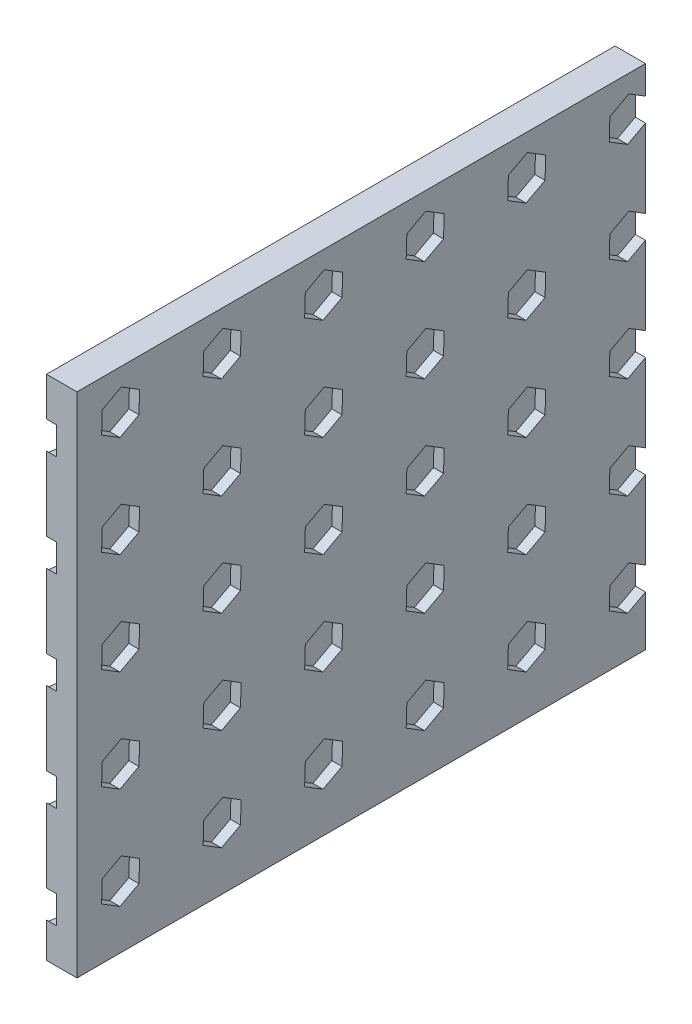
SolidWorks part; units mm, degrees
ref_plane "Front Plane" through (0, 0, 0) normal (0, 0, 1) x (1, 0, 0)
ref_plane "Top Plane" through (0, 0, 0) normal (0, 1, 0) x (1, 0, 0)
ref_plane "Right Plane" through (0, 0, 0) normal (1, 0, 0) x (0, 0, -1)
sketch "Sketch1" plane through (0, 0, 0) normal (1, 0, 0) x (0, 0, -1)
  line L1 (-28, 25) -> (28, 25)
  line L2 (-28, 25) -> (-28, -25)
  line L3 (-28, -25) -> (28, -25)
  line L4 (28, 25) -> (28, -25)
  line L5 (0, -25) -> (0, 25) construction
  line L6 (-28, 0) -> (28, 0) construction
  point P0 (0, 0)
  dimension "D1" = 56
  dimension "D2" = 50
extrude "Boss-Extrude1" add sketch "Sketch1" along normal blind 3
sketch "Sketch2" plane through (3, 0, 0) normal (1, 0, 0) x (0, 0, -1)
  line L0 (-11.8942, 19.989) -> (-11.829, 22.1127)
  line L1 (-21.8942, 19.989) -> (-21.829, 22.1127)
  line L2 (-21.829, 22.1127) -> (-23.6355, 23.231)
  line L3 (-23.6355, 23.231) -> (-25.5072, 22.2257)
  line L4 (-25.5072, 22.2257) -> (-25.5725, 20.102)
  line L5 (-25.5725, 20.102) -> (-23.766, 18.9837)
  line L6 (-23.766, 18.9837) -> (-21.8942, 19.989)
  line L7 (-11.829, 22.1127) -> (-13.6355, 23.231)
  line L8 (-13.6355, 23.231) -> (-15.5072, 22.2257)
  line L9 (-15.5072, 22.2257) -> (-15.5725, 20.102)
  line L10 (-15.5725, 20.102) -> (-13.766, 18.9837)
  line L11 (-13.766, 18.9837) -> (-11.8942, 19.989)
  line L12 (-1.8942, 19.989) -> (-1.829, 22.1127)
  line L13 (-1.829, 22.1127) -> (-3.6355, 23.231)
  line L14 (-3.6355, 23.231) -> (-5.5072, 22.2257)
  line L15 (-5.5072, 22.2257) -> (-5.5725, 20.102)
  line L16 (-5.5725, 20.102) -> (-3.766, 18.9837)
  line L17 (-3.766, 18.9837) -> (-1.8942, 19.989)
  line L18 (8.1058, 19.989) -> (8.171, 22.1127)
  line L19 (8.171, 22.1127) -> (6.3645, 23.231)
  line L20 (6.3645, 23.231) -> (4.4928, 22.2257)
  line L21 (4.4928, 22.2257) -> (4.4275, 20.102)
  line L22 (4.4275, 20.102) -> (6.234, 18.9837)
  line L23 (6.234, 18.9837) -> (8.1058, 19.989)
  line L24 (18.1058, 19.989) -> (18.171, 22.1127)
  line L25 (18.171, 22.1127) -> (16.3645, 23.231)
  line L26 (16.3645, 23.231) -> (14.4928, 22.2257)
  line L27 (14.4928, 22.2257) -> (14.4275, 20.102)
  line L28 (14.4275, 20.102) -> (16.234, 18.9837)
  line L29 (16.234, 18.9837) -> (18.1058, 19.989)
  line L30 (28.1058, 19.989) -> (28.171, 22.1127)
  line L31 (28.171, 22.1127) -> (26.3645, 23.231)
  line L32 (26.3645, 23.231) -> (24.4928, 22.2257)
  line L33 (24.4928, 22.2257) -> (24.4275, 20.102)
  line L34 (24.4275, 20.102) -> (26.234, 18.9837)
  line L35 (26.234, 18.9837) -> (28.1058, 19.989)
  line L36 (-11.8942, 9.989) -> (-11.829, 12.1127)
  line L37 (-11.829, 12.1127) -> (-13.6355, 13.231)
  line L38 (-13.6355, 13.231) -> (-15.5072, 12.2257)
  line L39 (-15.5072, 12.2257) -> (-15.5725, 10.102)
  line L40 (-15.5725, 10.102) -> (-13.766, 8.9837)
  line L41 (-13.766, 8.9837) -> (-11.8942, 9.989)
  line L42 (-1.8942, 9.989) -> (-1.829, 12.1127)
  line L43 (-1.829, 12.1127) -> (-3.6355, 13.231)
  line L44 (-3.6355, 13.231) -> (-5.5072, 12.2257)
  line L45 (-5.5072, 12.2257) -> (-5.5725, 10.102)
  line L46 (-5.5725, 10.102) -> (-3.766, 8.9837)
  line L47 (-3.766, 8.9837) -> (-1.8942, 9.989)
  line L48 (8.1058, 9.989) -> (8.171, 12.1127)
  line L49 (8.171, 12.1127) -> (6.3645, 13.231)
  line L50 (6.3645, 13.231) -> (4.4928, 12.2257)
  line L51 (4.4928, 12.2257) -> (4.4275, 10.102)
  line L52 (4.4275, 10.102) -> (6.234, 8.9837)
  line L53 (6.234, 8.9837) -> (8.1058, 9.989)
  line L54 (18.1058, 9.989) -> (18.171, 12.1127)
  line L55 (18.171, 12.1127) -> (16.3645, 13.231)
  line L56 (16.3645, 13.231) -> (14.4928, 12.2257)
  line L57 (14.4928, 12.2257) -> (14.4275, 10.102)
  line L58 (14.4275, 10.102) -> (16.234, 8.9837)
  line L59 (16.234, 8.9837) -> (18.1058, 9.989)
  line L60 (28.1058, 9.989) -> (28.171, 12.1127)
  line L61 (28.171, 12.1127) -> (26.3645, 13.231)
  line L62 (26.3645, 13.231) -> (24.4928, 12.2257)
  line L63 (24.4928, 12.2257) -> (24.4275, 10.102)
  line L64 (24.4275, 10.102) -> (26.234, 8.9837)
  line L65 (26.234, 8.9837) -> (28.1058, 9.989)
  line L66 (-11.8942, -0.011) -> (-11.829, 2.1127)
  line L67 (-11.829, 2.1127) -> (-13.6355, 3.231)
  line L68 (-13.6355, 3.231) -> (-15.5072, 2.2257)
  line L69 (-15.5072, 2.2257) -> (-15.5725, 0.102)
  line L70 (-15.5725, 0.102) -> (-13.766, -1.0163)
  line L71 (-13.766, -1.0163) -> (-11.8942, -0.011)
  line L72 (-1.8942, -0.011) -> (-1.829, 2.1127)
  line L73 (-1.829, 2.1127) -> (-3.6355, 3.231)
  line L74 (-3.6355, 3.231) -> (-5.5072, 2.2257)
  line L75 (-5.5072, 2.2257) -> (-5.5725, 0.102)
  line L76 (-5.5725, 0.102) -> (-3.766, -1.0163)
  line L77 (-3.766, -1.0163) -> (-1.8942, -0.011)
  line L78 (8.1058, -0.011) -> (8.171, 2.1127)
  line L79 (8.171, 2.1127) -> (6.3645, 3.231)
  line L80 (6.3645, 3.231) -> (4.4928, 2.2257)
  line L81 (4.4928, 2.2257) -> (4.4275, 0.102)
  line L82 (4.4275, 0.102) -> (6.234, -1.0163)
  line L83 (6.234, -1.0163) -> (8.1058, -0.011)
  line L84 (18.1058, -0.011) -> (18.171, 2.1127)
  line L85 (18.171, 2.1127) -> (16.3645, 3.231)
  line L86 (16.3645, 3.231) -> (14.4928, 2.2257)
  line L87 (14.4928, 2.2257) -> (14.4275, 0.102)
  line L88 (14.4275, 0.102) -> (16.234, -1.0163)
  line L89 (16.234, -1.0163) -> (18.1058, -0.011)
  line L90 (28.1058, -0.011) -> (28.171, 2.1127)
  line L91 (28.171, 2.1127) -> (26.3645, 3.231)
  line L92 (26.3645, 3.231) -> (24.4928, 2.2257)
  line L93 (24.4928, 2.2257) -> (24.4275, 0.102)
  line L94 (24.4275, 0.102) -> (26.234, -1.0163)
  line L95 (26.234, -1.0163) -> (28.1058, -0.011)
  line L96 (-11.8942, -10.011) -> (-11.829, -7.8873)
  line L97 (-11.829, -7.8873) -> (-13.6355, -6.769)
  line L98 (-13.6355, -6.769) -> (-15.5072, -7.7743)
  line L99 (-15.5072, -7.7743) -> (-15.5725, -9.898)
  line L100 (-15.5725, -9.898) -> (-13.766, -11.0163)
  line L101 (-13.766, -11.0163) -> (-11.8942, -10.011)
  line L102 (-1.8942, -10.011) -> (-1.829, -7.8873)
  line L103 (-1.829, -7.8873) -> (-3.6355, -6.769)
  line L104 (-3.6355, -6.769) -> (-5.5072, -7.7743)
  line L105 (-5.5072, -7.7743) -> (-5.5725, -9.898)
  line L106 (-5.5725, -9.898) -> (-3.766, -11.0163)
  line L107 (-3.766, -11.0163) -> (-1.8942, -10.011)
  line L108 (8.1058, -10.011) -> (8.171, -7.8873)
  line L109 (8.171, -7.8873) -> (6.3645, -6.769)
  line L110 (6.3645, -6.769) -> (4.4928, -7.7743)
  line L111 (4.4928, -7.7743) -> (4.4275, -9.898)
  line L112 (4.4275, -9.898) -> (6.234, -11.0163)
  line L113 (6.234, -11.0163) -> (8.1058, -10.011)
  line L114 (18.1058, -10.011) -> (18.171, -7.8873)
  line L115 (18.171, -7.8873) -> (16.3645, -6.769)
  line L116 (16.3645, -6.769) -> (14.4928, -7.7743)
  line L117 (14.4928, -7.7743) -> (14.4275, -9.898)
  line L118 (14.4275, -9.898) -> (16.234, -11.0163)
  line L119 (16.234, -11.0163) -> (18.1058, -10.011)
  line L120 (28.1058, -10.011) -> (28.171, -7.8873)
  line L121 (28.171, -7.8873) -> (26.3645, -6.769)
  line L122 (26.3645, -6.769) -> (24.4928, -7.7743)
  line L123 (24.4928, -7.7743) -> (24.4275, -9.898)
  line L124 (24.4275, -9.898) -> (26.234, -11.0163)
  line L125 (26.234, -11.0163) -> (28.1058, -10.011)
  line L126 (-11.8942, -20.011) -> (-11.829, -17.8873)
  line L127 (-11.829, -17.8873) -> (-13.6355, -16.769)
  line L128 (-13.6355, -16.769) -> (-15.5072, -17.7743)
  line L129 (-15.5072, -17.7743) -> (-15.5725, -19.898)
  line L130 (-15.5725, -19.898) -> (-13.766, -21.0163)
  line L131 (-13.766, -21.0163) -> (-11.8942, -20.011)
  line L132 (-1.8942, -20.011) -> (-1.829, -17.8873)
  line L133 (-1.829, -17.8873) -> (-3.6355, -16.769)
  line L134 (-3.6355, -16.769) -> (-5.5072, -17.7743)
  line L135 (-5.5072, -17.7743) -> (-5.5725, -19.898)
  line L136 (-5.5725, -19.898) -> (-3.766, -21.0163)
  line L137 (-3.766, -21.0163) -> (-1.8942, -20.011)
  line L138 (8.1058, -20.011) -> (8.171, -17.8873)
  line L139 (8.171, -17.8873) -> (6.3645, -16.769)
  line L140 (6.3645, -16.769) -> (4.4928, -17.7743)
  line L141 (4.4928, -17.7743) -> (4.4275, -19.898)
  line L142 (4.4275, -19.898) -> (6.234, -21.0163)
  line L143 (6.234, -21.0163) -> (8.1058, -20.011)
  line L144 (18.1058, -20.011) -> (18.171, -17.8873)
  line L145 (18.171, -17.8873) -> (16.3645, -16.769)
  line L146 (16.3645, -16.769) -> (14.4928, -17.7743)
  line L147 (14.4928, -17.7743) -> (14.4275, -19.898)
  line L148 (14.4275, -19.898) -> (16.234, -21.0163)
  line L149 (16.234, -21.0163) -> (18.1058, -20.011)
  line L150 (28.1058, -20.011) -> (28.171, -17.8873)
  line L151 (28.171, -17.8873) -> (26.3645, -16.769)
  line L152 (26.3645, -16.769) -> (24.4928, -17.7743)
  line L153 (24.4928, -17.7743) -> (24.4275, -19.898)
  line L154 (24.4275, -19.898) -> (26.234, -21.0163)
  line L155 (26.234, -21.0163) -> (28.1058, -20.011)
  line L156 (-21.8942, 9.989) -> (-21.829, 12.1127)
  line L157 (-21.829, 12.1127) -> (-23.6355, 13.231)
  line L158 (-23.6355, 13.231) -> (-25.5072, 12.2257)
  line L159 (-25.5072, 12.2257) -> (-25.5725, 10.102)
  line L160 (-25.5725, 10.102) -> (-23.766, 8.9837)
  line L161 (-23.766, 8.9837) -> (-21.8942, 9.989)
  line L162 (-21.8942, -0.011) -> (-21.829, 2.1127)
  line L163 (-21.829, 2.1127) -> (-23.6355, 3.231)
  line L164 (-23.6355, 3.231) -> (-25.5072, 2.2257)
  line L165 (-25.5072, 2.2257) -> (-25.5725, 0.102)
  line L166 (-25.5725, 0.102) -> (-23.766, -1.0163)
  line L167 (-23.766, -1.0163) -> (-21.8942, -0.011)
  line L168 (-21.8942, -10.011) -> (-21.829, -7.8873)
  line L169 (-21.829, -7.8873) -> (-23.6355, -6.769)
  line L170 (-23.6355, -6.769) -> (-25.5072, -7.7743)
  line L171 (-25.5072, -7.7743) -> (-25.5725, -9.898)
  line L172 (-25.5725, -9.898) -> (-23.766, -11.0163)
  line L173 (-23.766, -11.0163) -> (-21.8942, -10.011)
  line L174 (-21.8942, -20.011) -> (-21.829, -17.8873)
  line L175 (-21.829, -17.8873) -> (-23.6355, -16.769)
  line L176 (-23.6355, -16.769) -> (-25.5072, -17.7743)
  line L177 (-25.5072, -17.7743) -> (-25.5725, -19.898)
  line L178 (-25.5725, -19.898) -> (-23.766, -21.0163)
  line L179 (-23.766, -21.0163) -> (-21.8942, -20.011)
  circle A0 centre (-23.7007, 21.1074) radius 1.84 construction
  dimension "D1" = 3.68
  dimension "D2" = 6
  dimension "D3" = 5
extrude "Cut-Extrude1" cut sketch "Sketch2" against normal blind 1
sketch "Sketch3" plane through (0, 0, 0) normal (-1, 0, 0) x (0, 0, 1)
  line L0 (-12.0818, 18.255) -> (-11.2655, 20.2166)
  line L1 (-22.0818, 18.255) -> (-21.2655, 20.2166)
  line L2 (-21.2655, 20.2166) -> (-22.5561, 21.9043)
  line L3 (-22.5561, 21.9043) -> (-24.663, 21.6304)
  line L4 (-24.663, 21.6304) -> (-25.4793, 19.6689)
  line L5 (-25.4793, 19.6689) -> (-24.1887, 17.9811)
  line L6 (-24.1887, 17.9811) -> (-22.0818, 18.255)
  line L7 (-11.2655, 20.2166) -> (-12.5561, 21.9043)
  line L8 (-12.5561, 21.9043) -> (-14.663, 21.6304)
  line L9 (-14.663, 21.6304) -> (-15.4793, 19.6689)
  line L10 (-15.4793, 19.6689) -> (-14.1887, 17.9811)
  line L11 (-14.1887, 17.9811) -> (-12.0818, 18.255)
  line L12 (-2.0818, 18.255) -> (-1.2655, 20.2166)
  line L13 (-1.2655, 20.2166) -> (-2.5561, 21.9043)
  line L14 (-2.5561, 21.9043) -> (-4.663, 21.6304)
  line L15 (-4.663, 21.6304) -> (-5.4793, 19.6689)
  line L16 (-5.4793, 19.6689) -> (-4.1887, 17.9811)
  line L17 (-4.1887, 17.9811) -> (-2.0818, 18.255)
  line L18 (7.9182, 18.255) -> (8.7345, 20.2166)
  line L19 (8.7345, 20.2166) -> (7.4439, 21.9043)
  line L20 (7.4439, 21.9043) -> (5.337, 21.6304)
  line L21 (5.337, 21.6304) -> (4.5207, 19.6689)
  line L22 (4.5207, 19.6689) -> (5.8113, 17.9811)
  line L23 (5.8113, 17.9811) -> (7.9182, 18.255)
  line L24 (17.9182, 18.255) -> (18.7345, 20.2166)
  line L25 (18.7345, 20.2166) -> (17.4439, 21.9043)
  line L26 (17.4439, 21.9043) -> (15.337, 21.6304)
  line L27 (15.337, 21.6304) -> (14.5207, 19.6689)
  line L28 (14.5207, 19.6689) -> (15.8113, 17.9811)
  line L29 (15.8113, 17.9811) -> (17.9182, 18.255)
  line L30 (27.9182, 18.255) -> (28.7345, 20.2166)
  line L31 (28.7345, 20.2166) -> (27.4439, 21.9043)
  line L32 (27.4439, 21.9043) -> (25.337, 21.6304)
  line L33 (25.337, 21.6304) -> (24.5207, 19.6689)
  line L34 (24.5207, 19.6689) -> (25.8113, 17.9811)
  line L35 (25.8113, 17.9811) -> (27.9182, 18.255)
  line L36 (-12.0818, 8.255) -> (-11.2655, 10.2166)
  line L37 (-11.2655, 10.2166) -> (-12.5561, 11.9043)
  line L38 (-12.5561, 11.9043) -> (-14.663, 11.6304)
  line L39 (-14.663, 11.6304) -> (-15.4793, 9.6689)
  line L40 (-15.4793, 9.6689) -> (-14.1887, 7.9811)
  line L41 (-14.1887, 7.9811) -> (-12.0818, 8.255)
  line L42 (-2.0818, 8.255) -> (-1.2655, 10.2166)
  line L43 (-1.2655, 10.2166) -> (-2.5561, 11.9043)
  line L44 (-2.5561, 11.9043) -> (-4.663, 11.6304)
  line L45 (-4.663, 11.6304) -> (-5.4793, 9.6689)
  line L46 (-5.4793, 9.6689) -> (-4.1887, 7.9811)
  line L47 (-4.1887, 7.9811) -> (-2.0818, 8.255)
  line L48 (7.9182, 8.255) -> (8.7345, 10.2166)
  line L49 (8.7345, 10.2166) -> (7.4439, 11.9043)
  line L50 (7.4439, 11.9043) -> (5.337, 11.6304)
  line L51 (5.337, 11.6304) -> (4.5207, 9.6689)
  line L52 (4.5207, 9.6689) -> (5.8113, 7.9811)
  line L53 (5.8113, 7.9811) -> (7.9182, 8.255)
  line L54 (17.9182, 8.255) -> (18.7345, 10.2166)
  line L55 (18.7345, 10.2166) -> (17.4439, 11.9043)
  line L56 (17.4439, 11.9043) -> (15.337, 11.6304)
  line L57 (15.337, 11.6304) -> (14.5207, 9.6689)
  line L58 (14.5207, 9.6689) -> (15.8113, 7.9811)
  line L59 (15.8113, 7.9811) -> (17.9182, 8.255)
  line L60 (27.9182, 8.255) -> (28.7345, 10.2166)
  line L61 (28.7345, 10.2166) -> (27.4439, 11.9043)
  line L62 (27.4439, 11.9043) -> (25.337, 11.6304)
  line L63 (25.337, 11.6304) -> (24.5207, 9.6689)
  line L64 (24.5207, 9.6689) -> (25.8113, 7.9811)
  line L65 (25.8113, 7.9811) -> (27.9182, 8.255)
  line L66 (-12.0818, -1.745) -> (-11.2655, 0.2166)
  line L67 (-11.2655, 0.2166) -> (-12.5561, 1.9043)
  line L68 (-12.5561, 1.9043) -> (-14.663, 1.6304)
  line L69 (-14.663, 1.6304) -> (-15.4793, -0.3311)
  line L70 (-15.4793, -0.3311) -> (-14.1887, -2.0189)
  line L71 (-14.1887, -2.0189) -> (-12.0818, -1.745)
  line L72 (-2.0818, -1.745) -> (-1.2655, 0.2166)
  line L73 (-1.2655, 0.2166) -> (-2.5561, 1.9043)
  line L74 (-2.5561, 1.9043) -> (-4.663, 1.6304)
  line L75 (-4.663, 1.6304) -> (-5.4793, -0.3311)
  line L76 (-5.4793, -0.3311) -> (-4.1887, -2.0189)
  line L77 (-4.1887, -2.0189) -> (-2.0818, -1.745)
  line L78 (7.9182, -1.745) -> (8.7345, 0.2166)
  line L79 (8.7345, 0.2166) -> (7.4439, 1.9043)
  line L80 (7.4439, 1.9043) -> (5.337, 1.6304)
  line L81 (5.337, 1.6304) -> (4.5207, -0.3311)
  line L82 (4.5207, -0.3311) -> (5.8113, -2.0189)
  line L83 (5.8113, -2.0189) -> (7.9182, -1.745)
  line L84 (17.9182, -1.745) -> (18.7345, 0.2166)
  line L85 (18.7345, 0.2166) -> (17.4439, 1.9043)
  line L86 (17.4439, 1.9043) -> (15.337, 1.6304)
  line L87 (15.337, 1.6304) -> (14.5207, -0.3311)
  line L88 (14.5207, -0.3311) -> (15.8113, -2.0189)
  line L89 (15.8113, -2.0189) -> (17.9182, -1.745)
  line L90 (27.9182, -1.745) -> (28.7345, 0.2166)
  line L91 (28.7345, 0.2166) -> (27.4439, 1.9043)
  line L92 (27.4439, 1.9043) -> (25.337, 1.6304)
  line L93 (25.337, 1.6304) -> (24.5207, -0.3311)
  line L94 (24.5207, -0.3311) -> (25.8113, -2.0189)
  line L95 (25.8113, -2.0189) -> (27.9182, -1.745)
  line L96 (-12.0818, -11.745) -> (-11.2655, -9.7834)
  line L97 (-11.2655, -9.7834) -> (-12.5561, -8.0957)
  line L98 (-12.5561, -8.0957) -> (-14.663, -8.3696)
  line L99 (-14.663, -8.3696) -> (-15.4793, -10.3311)
  line L100 (-15.4793, -10.3311) -> (-14.1887, -12.0189)
  line L101 (-14.1887, -12.0189) -> (-12.0818, -11.745)
  line L102 (-2.0818, -11.745) -> (-1.2655, -9.7834)
  line L103 (-1.2655, -9.7834) -> (-2.5561, -8.0957)
  line L104 (-2.5561, -8.0957) -> (-4.663, -8.3696)
  line L105 (-4.663, -8.3696) -> (-5.4793, -10.3311)
  line L106 (-5.4793, -10.3311) -> (-4.1887, -12.0189)
  line L107 (-4.1887, -12.0189) -> (-2.0818, -11.745)
  line L108 (7.9182, -11.745) -> (8.7345, -9.7834)
  line L109 (8.7345, -9.7834) -> (7.4439, -8.0957)
  line L110 (7.4439, -8.0957) -> (5.337, -8.3696)
  line L111 (5.337, -8.3696) -> (4.5207, -10.3311)
  line L112 (4.5207, -10.3311) -> (5.8113, -12.0189)
  line L113 (5.8113, -12.0189) -> (7.9182, -11.745)
  line L114 (17.9182, -11.745) -> (18.7345, -9.7834)
  line L115 (18.7345, -9.7834) -> (17.4439, -8.0957)
  line L116 (17.4439, -8.0957) -> (15.337, -8.3696)
  line L117 (15.337, -8.3696) -> (14.5207, -10.3311)
  line L118 (14.5207, -10.3311) -> (15.8113, -12.0189)
  line L119 (15.8113, -12.0189) -> (17.9182, -11.745)
  line L120 (27.9182, -11.745) -> (28.7345, -9.7834)
  line L121 (28.7345, -9.7834) -> (27.4439, -8.0957)
  line L122 (27.4439, -8.0957) -> (25.337, -8.3696)
  line L123 (25.337, -8.3696) -> (24.5207, -10.3311)
  line L124 (24.5207, -10.3311) -> (25.8113, -12.0189)
  line L125 (25.8113, -12.0189) -> (27.9182, -11.745)
  line L126 (-12.0818, -21.745) -> (-11.2655, -19.7834)
  line L127 (-11.2655, -19.7834) -> (-12.5561, -18.0957)
  line L128 (-12.5561, -18.0957) -> (-14.663, -18.3696)
  line L129 (-14.663, -18.3696) -> (-15.4793, -20.3311)
  line L130 (-15.4793, -20.3311) -> (-14.1887, -22.0189)
  line L131 (-14.1887, -22.0189) -> (-12.0818, -21.745)
  line L132 (-2.0818, -21.745) -> (-1.2655, -19.7834)
  line L133 (-1.2655, -19.7834) -> (-2.5561, -18.0957)
  line L134 (-2.5561, -18.0957) -> (-4.663, -18.3696)
  line L135 (-4.663, -18.3696) -> (-5.4793, -20.3311)
  line L136 (-5.4793, -20.3311) -> (-4.1887, -22.0189)
  line L137 (-4.1887, -22.0189) -> (-2.0818, -21.745)
  line L138 (7.9182, -21.745) -> (8.7345, -19.7834)
  line L139 (8.7345, -19.7834) -> (7.4439, -18.0957)
  line L140 (7.4439, -18.0957) -> (5.337, -18.3696)
  line L141 (5.337, -18.3696) -> (4.5207, -20.3311)
  line L142 (4.5207, -20.3311) -> (5.8113, -22.0189)
  line L143 (5.8113, -22.0189) -> (7.9182, -21.745)
  line L144 (17.9182, -21.745) -> (18.7345, -19.7834)
  line L145 (18.7345, -19.7834) -> (17.4439, -18.0957)
  line L146 (17.4439, -18.0957) -> (15.337, -18.3696)
  line L147 (15.337, -18.3696) -> (14.5207, -20.3311)
  line L148 (14.5207, -20.3311) -> (15.8113, -22.0189)
  line L149 (15.8113, -22.0189) -> (17.9182, -21.745)
  line L150 (27.9182, -21.745) -> (28.7345, -19.7834)
  line L151 (28.7345, -19.7834) -> (27.4439, -18.0957)
  line L152 (27.4439, -18.0957) -> (25.337, -18.3696)
  line L153 (25.337, -18.3696) -> (24.5207, -20.3311)
  line L154 (24.5207, -20.3311) -> (25.8113, -22.0189)
  line L155 (25.8113, -22.0189) -> (27.9182, -21.745)
  line L156 (-22.0818, 8.255) -> (-21.2655, 10.2166)
  line L157 (-21.2655, 10.2166) -> (-22.5561, 11.9043)
  line L158 (-22.5561, 11.9043) -> (-24.663, 11.6304)
  line L159 (-24.663, 11.6304) -> (-25.4793, 9.6689)
  line L160 (-25.4793, 9.6689) -> (-24.1887, 7.9811)
  line L161 (-24.1887, 7.9811) -> (-22.0818, 8.255)
  line L162 (-22.0818, -1.745) -> (-21.2655, 0.2166)
  line L163 (-21.2655, 0.2166) -> (-22.5561, 1.9043)
  line L164 (-22.5561, 1.9043) -> (-24.663, 1.6304)
  line L165 (-24.663, 1.6304) -> (-25.4793, -0.3311)
  line L166 (-25.4793, -0.3311) -> (-24.1887, -2.0189)
  line L167 (-24.1887, -2.0189) -> (-22.0818, -1.745)
  line L168 (-22.0818, -11.745) -> (-21.2655, -9.7834)
  line L169 (-21.2655, -9.7834) -> (-22.5561, -8.0957)
  line L170 (-22.5561, -8.0957) -> (-24.663, -8.3696)
  line L171 (-24.663, -8.3696) -> (-25.4793, -10.3311)
  line L172 (-25.4793, -10.3311) -> (-24.1887, -12.0189)
  line L173 (-24.1887, -12.0189) -> (-22.0818, -11.745)
  line L174 (-22.0818, -21.745) -> (-21.2655, -19.7834)
  line L175 (-21.2655, -19.7834) -> (-22.5561, -18.0957)
  line L176 (-22.5561, -18.0957) -> (-24.663, -18.3696)
  line L177 (-24.663, -18.3696) -> (-25.4793, -20.3311)
  line L178 (-25.4793, -20.3311) -> (-24.1887, -22.0189)
  line L179 (-24.1887, -22.0189) -> (-22.0818, -21.745)
  circle A0 centre (-23.3724, 19.9427) radius 1.84 construction
  dimension "D1" = 3.68
  dimension "D2" = 6
  dimension "D3" = 5
extrude "Cut-Extrude2" cut sketch "Sketch3" against normal blind 1
